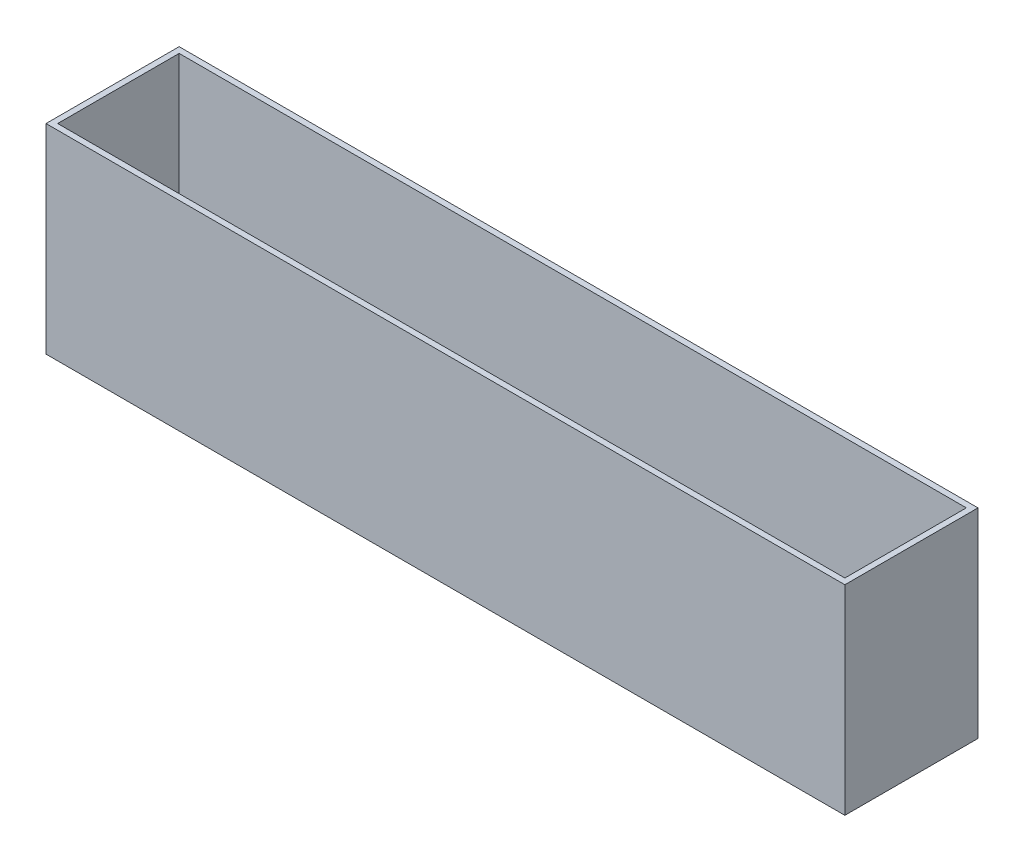
SolidWorks part; units mm, degrees
material "Acrylic (Medium-high impact)"
ref_plane "Front Plane" through (0, 0, 0) normal (0, 0, 1) x (1, 0, 0)
ref_plane "Top Plane" through (0, 0, 0) normal (0, 1, 0) x (1, 0, 0)
ref_plane "Right Plane" through (0, 0, 0) normal (1, 0, 0) x (0, 0, -1)
sketch "Sketch1" plane through (0, 0, 0) normal (0, 1, 0) x (1, 0, 0)
  line L1 (0, 0) -> (1200, 0)
  line L2 (0, 0) -> (0, 200)
  line L3 (0, 200) -> (1200, 200)
  line L4 (1200, 0) -> (1200, 200)
  dimension "D1" = 1200
  dimension "D2" = 200
extrude "Boss-Extrude1" add sketch "Sketch1" along normal blind 300
sketch "Sketch2" plane through (0, 300, 0) normal (0, 1, 0) x (1, 0, 0)
  line L0 (0, 200) -> (0, 0) construction
  line L1 (8.763, 191.237) -> (1191.237, 191.237)
  line L2 (8.763, 191.237) -> (8.763, 8.763)
  line L3 (8.763, 8.763) -> (1191.237, 8.763)
  line L4 (1191.237, 191.237) -> (1191.237, 8.763)
  line L5 (1200, 0) -> (1200, 200) construction
  line L6 (1200, 200) -> (0, 200) construction
  line L7 (0, 0) -> (1200, 0) construction
  dimension "D1" = 8.763
  dimension "D2" = 8.763
  dimension "D3" = 8.763
  dimension "D4" = 8.763
extrude "Cut-Extrude1" cut sketch "Sketch2" against normal blind 291.237
